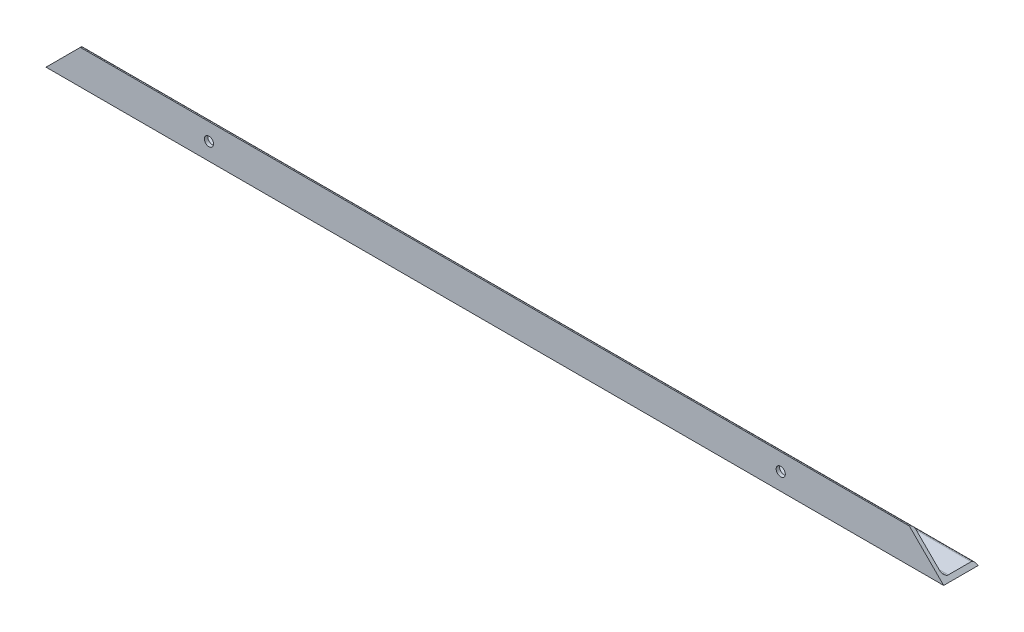
SolidWorks part; units mm, degrees
ref_plane "Front Plane" through (0, 0, 0) normal (0, 0, 1) x (1, 0, 0)
ref_plane "Top Plane" through (0, 0, 0) normal (0, 1, 0) x (1, 0, 0)
ref_plane "Right Plane" through (0, 0, 0) normal (1, 0, 0) x (0, 0, -1)
sketch "Sketch1" plane through (0, 0, 0) normal (0, 1, 0) x (1, 0, 0)
  line L0 (0, 0) -> (1570, 0)
  dimension "D1" = 1570
other "L angle (equal) 60X60X6(3)"
ref_plane "Plane1" through (0, 0, 0) normal (1, 0, 0) x (0, 0, -1)
sketch "Sketch17" plane through (0, 0, 0) normal (1, 0, 0) x (0, 0, -1)
  line L0 (0, 60) -> (0, 0)
  line L2 (6, 54) -> (6, 14)
  line L3 (14, 6) -> (54, 6)
  line L5 (60, 0) -> (0, 0)
  arc A0 (6, 54) -> (0, 60) centre (0, 54) ccw
  arc A1 (60, 0) -> (54, 6) centre (54, 0) ccw
  arc A2 (14, 6) -> (6, 14) centre (14, 14) cw
  point P8 (0, 30)
  point P9 (30, 0)
  point P10 (0, 0)
  dimension "Radius_2" = 6
  dimension "Radius_1" = 8
  dimension "V_leg" = 60
  dimension "H_leg" = 60
  dimension "thickness" = 6
sketch "Sketch14" plane through (0, 0, 0) normal (0, 0, 1) x (1, 0, 0)
  line L0 (1570, 0) -> (1570, 60)
  line L3 (1510, 60) -> (1570, 0)
  line L4 (0, 60) -> (0, 0)
  line L5 (0, 0) -> (1570, 0)
  line L6 (1570, 0) -> (1570, 60)
  line L7 (1570, 60) -> (0, 60)
  line L10 (1570, 0) -> (1570, 60) construction
  line L11 (1570, 60) -> (1510, 60)
  line L13 (1570, 60) -> (1510, 60) construction
  line L14 (0, 60) -> (0, 0) construction
  line L15 (0, 60) -> (0, 0)
  line L18 (0, 60) -> (60, 60)
  line L19 (1570, 60) -> (1270, 60) construction
  line L20 (1570, 60) -> (0, 60) construction
  line L21 (60, 60) -> (0, 0)
  line L22 (60, 60) -> (1510, 60) construction
  line L23 (60, 60) -> (0, 60) construction
  line L24 (0, 0) -> (1570, 0) construction
  line L25 (0, 0) -> (270, 0) construction
  line L26 (270, 60) -> (0, 60) construction
  line L27 (758.8012, 0) -> (1570, 0) construction
  line L28 (785, 60) -> (785, -104.1464) construction
  circle A3 centre (285, 30) radius 8
  circle A4 centre (1285, 30) radius 8
  dimension "D3" = 60
  dimension "D5" = 500
  dimension "D4" = 500
  dimension "D2" = 60
  dimension "D1" = 0
extrude "Cut-Extrude1" cut sketch "Sketch14" against normal through all
